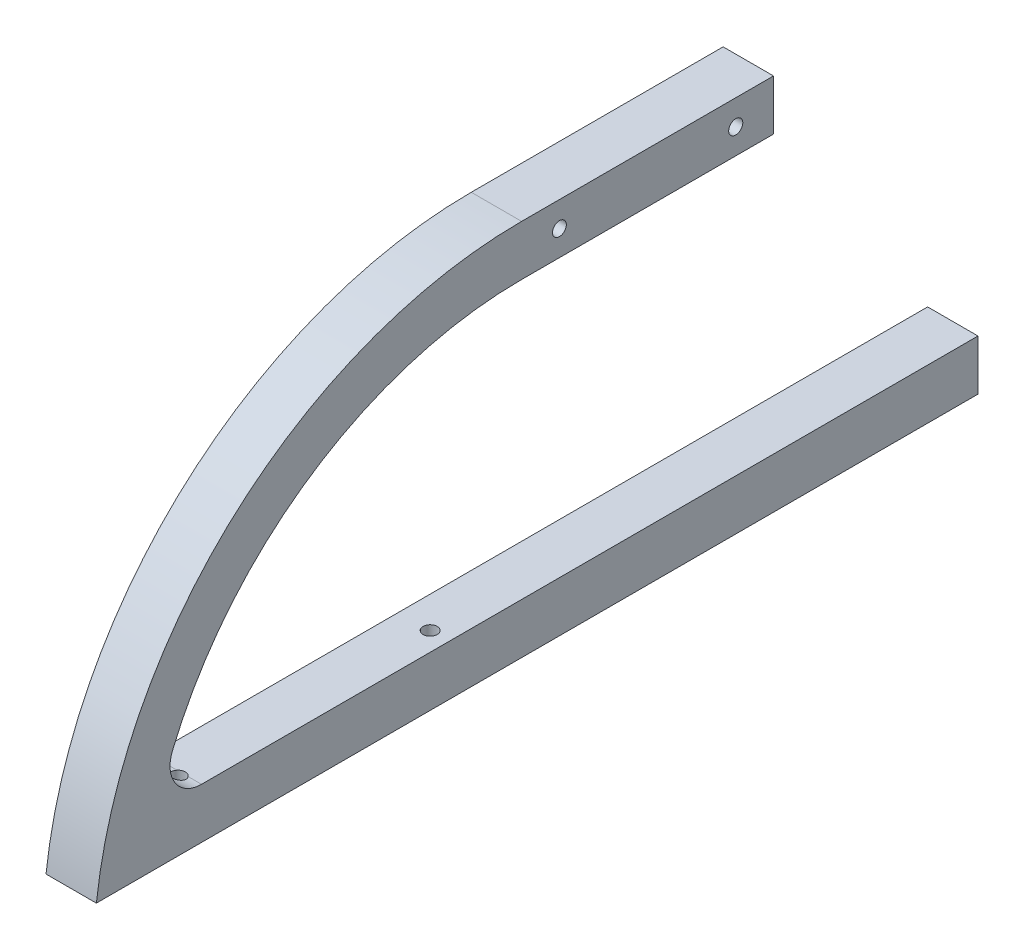
SolidWorks part; units mm, degrees
material "1060 Alloy"
ref_plane "Front Plane" through (0, 0, 0) normal (0, 0, 1) x (1, 0, 0)
ref_plane "Top Plane" through (0, 0, 0) normal (0, 1, 0) x (1, 0, 0)
ref_plane "Right Plane" through (0, 0, 0) normal (1, 0, 0) x (0, 0, -1)
sketch "Sketch1" plane through (0, 0, 0) normal (1, 0, 0) x (0, 0, -1)
  line L0 (-136.5603, -76.2) -> (41.2397, -76.2)
  line L1 (0, 0) -> (-50.8, 0)
  line L2 (0, 0) -> (0, -10.16)
  line L3 (0, -10.16) -> (-50.8, -10.16)
  line L5 (-115.358, -66.04) -> (41.2397, -66.04)
  line L6 (41.2397, -66.04) -> (41.2397, -76.2)
  line L7 (-25.4, 0) -> (-25.4, -10.16) construction
  arc A0 (-50.8, 0) -> (-136.5603, -76.2) centre (-50.8, -86.36) ccw
  arc A1 (-50.8, -10.16) -> (-121.2269, -57.2655) centre (-50.8, -86.36) ccw
  arc A2 (-115.358, -66.04) -> (-121.2269, -57.2655) centre (-115.358, -59.69) cw
  dimension "D1" = 10.16
  dimension "D5" = 76.2
  dimension "D7" = 6.35
  dimension "D2" = 50.8
  dimension "D3" = 177.8
  dimension "D4" = 10.16
  dimension "D6" = 76.2
extrude "Boss-Extrude1" add sketch "Sketch1" along normal blind 10.16
sketch "Sketch2" plane through (10.16, 0, 0) normal (1, 0, 0) x (0, 0, -1)
  line L0 (0, 0) -> (-50.8, 0) construction
  line L2 (0, -10.16) -> (0, 0) construction
  circle A0 centre (-7.62, -5.08) radius 1.4224
  dimension "D1" = 2.8448
  dimension "D2" = 5.08
  dimension "D3" = 7.62
extrude "Cut-Extrude2" cut sketch "Sketch2" against normal through all
sketch "Sketch3" plane through (0, -76.2, 0) normal (0, -1, 0) x (1, 0, 0)
  line L0 (10.16, 136.5603) -> (10.16, -41.2397) construction
  line L1 (10.16, 136.5603) -> (0, 136.5603) construction
  circle A0 centre (6.35, 116.2403) radius 1.4224
  circle A1 centre (6.35, 65.4403) radius 1.4224
  dimension "D1" = 3.81
  dimension "D2" = 2.8448
  dimension "D4" = 2.8448
  dimension "D3" = 20.32
  dimension "D5" = 3.81
  dimension "D6" = 50.8
extrude "Cut-Extrude3" cut sketch "Sketch3" against normal up to next
hole_wizard "CSK for #3 Flat Head Machine Screw (100)1" positions "Sketch4" profile "Sketch5" countersink size "#3" standard "ANSI Inch" end condition through all
sketch "Sketch4" plane through (0, 0, 0) normal (-1, 0, 0) x (0, 0, 1)
  point P0 (7.62, -5.08)
sketch "Sketch5" plane through (0, -5.08, 7.62) normal (0, 1, 0) x (0, 0, 1)
  line L0 (0, 0) -> (0, 10.16)
  line L1 (0, 10.16) -> (1.397, 10.16)
  line L2 (1.397, 10.16) -> (1.397, 2.8781)
  line L3 (1.397, 2.8781) -> (3.8989, 0)
  line L5 (3.8989, 0) -> (0, 0)
  line L6 (-1.397, 2.8781) -> (-3.8989, 0) construction
  line L11 (0, -6.35) -> (0, 107.95) construction
  dimension "Thru Hole Dia." = 2.794
  dimension "Thru Hole Depth" = 10.16
  dimension "Near C'Sink Dia." = 7.7978
  dimension "Near C'Sink Angle" = 82
ref_plane "Plane1" through (0, 0, 25.4) normal (0, 0, -1) x (-1, 0, 0)
mirror "Mirror1" about plane through (0, 0, 25.4) normal (0, 0, -1) of "CSK for #3 Flat Head Machine Screw (100)1"
